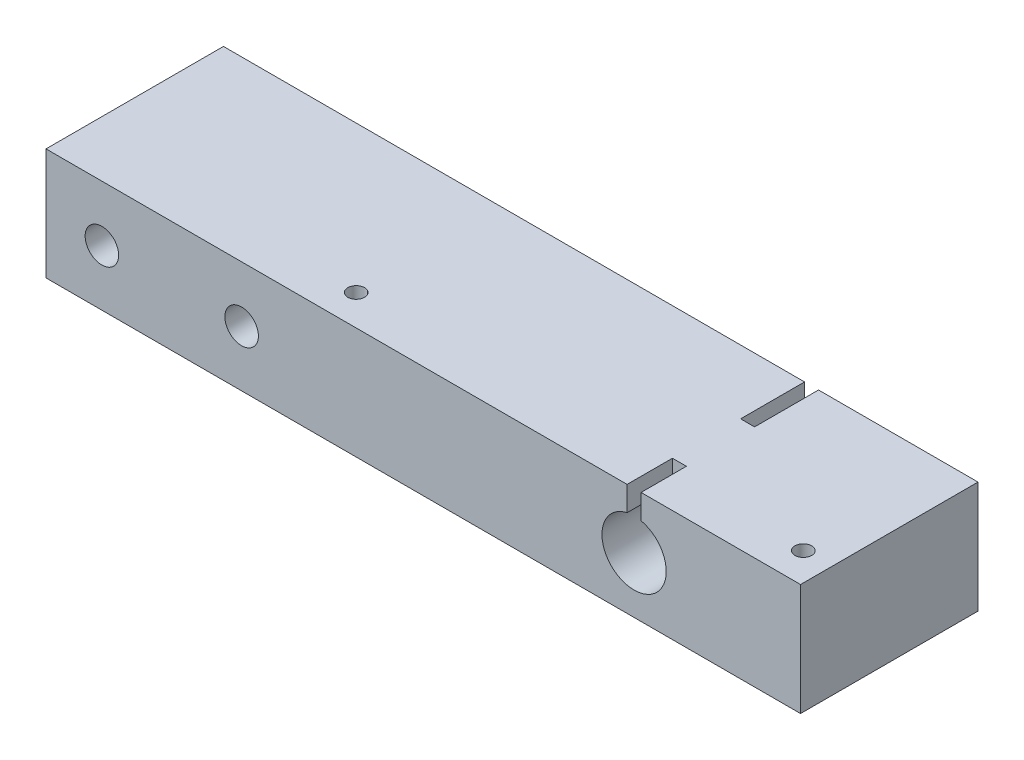
SolidWorks part; units mm, degrees
ref_plane "Front Plane" through (0, 0, 0) normal (0, 0, 1) x (1, 0, 0)
ref_plane "Top Plane" through (0, 0, 0) normal (0, 1, 0) x (1, 0, 0)
ref_plane "Right Plane" through (0, 0, 0) normal (1, 0, 0) x (0, 0, -1)
sketch "Sketch1" plane through (0, 0, 0) normal (0, 0, 1) x (1, 0, 0)
  line L1 (0, 0) -> (54, 0)
  line L2 (0, 0) -> (0, 8)
  line L3 (0, 8) -> (54, 8)
  line L4 (54, 0) -> (54, 8)
extrude "Boss-Extrude1" add sketch "Sketch1" along normal blind 12.7
sketch "Sketch3" plane through (0, 8, 0) normal (0, 1, 0) x (1, 0, 0)
  line L0 (42, -17.996) -> (42, 5.2833) construction
  line L2 (54, -6.35) -> (-1.1589, -6.35) construction
  line L3 (54, -12.7) -> (54, 0) construction
  line L4 (54, -12.7) -> (0, -12.7) construction
  line L5 (42.5877, -12.7) -> (41.5877, -12.7)
  line L6 (42.5877, -12.7) -> (42.5877, -9.4569)
  line L7 (42.5877, -9.4569) -> (41.5877, -9.4569)
  line L8 (41.5877, -12.7) -> (41.5877, -9.4569)
  line L10 (42.5877, 0) -> (41.5877, 0)
  line L11 (42.5877, 0) -> (42.5877, -4.5774)
  line L12 (42.5877, -4.5774) -> (41.5877, -4.5774)
  line L13 (41.5877, 0) -> (41.5877, -4.5774)
extrude "Cut-Extrude1" cut sketch "Sketch3" against normal blind 2
sketch "Sketch4" plane through (0, 0, 12.7) normal (0, 0, 1) x (1, 0, 0)
  line L0 (54, 4) -> (0, 4) construction
  line L1 (54, 0) -> (54, 8) construction
  line L2 (0, 8) -> (0, 0) construction
  line L3 (42.0877, 0) -> (42.0877, 8) construction
  line L4 (42.5877, 0) -> (41.5877, 0) construction
  line L5 (42.5877, 8) -> (41.5877, 8) construction
  circle A0 centre (42.0877, 4) radius 2.3
extrude "Cut-Extrude2" cut sketch "Sketch4" against normal through all
sketch "Sketch5" plane through (0, 8, 0) normal (0, 1, 0) x (1, 0, 0)
  line L0 (54, -10.5) -> (-2.4296, -10.5) construction
  line L1 (54, -12.7) -> (54, 0) construction
  line L2 (52, -19.5209) -> (52, 7.0115) construction
  circle A0 centre (52, -10.5) radius 0.6
  circle A1 centre (20, -10.5) radius 0.6
  dimension "D1" = 32
extrude "Cut-Extrude3" cut sketch "Sketch5" against normal through all
sketch "Sketch6" plane through (0, 0, 12.7) normal (0, 0, 1) x (1, 0, 0)
  line L0 (54, 4) -> (0, 4) construction
  line L1 (54, 0) -> (54, 8) construction
  line L2 (0, 8) -> (0, 0) construction
  line L3 (4, 0) -> (4, 8) construction
  line L4 (0, 0) -> (54, 0) construction
  line L5 (41.5877, 8) -> (0, 8) construction
  circle A0 centre (4, 4) radius 1.2
  circle A1 centre (14, 4) radius 1.2
  dimension "D1" = 10
extrude "Cut-Extrude4" cut sketch "Sketch6" against normal through all
sketch "Sketch10" plane through (0, 8, 0) normal (0, 1, 0) x (1, 0, 0)
  line L0 (54, -6.35) -> (0, -6.35) construction
  line L1 (54, -12.7) -> (54, 0) construction
  line L2 (0, -12.7) -> (0, 0) construction
  line L3 (42.0877, 0) -> (42.0877, -12.7) construction
  line L4 (44.3877, 0) -> (39.7877, 0) construction
  line L5 (39.7877, -12.7) -> (44.3877, -12.7) construction
  line L6 (42.0877, -6.35) -> (36.2418, -12.7) construction
  line L7 (41.5877, -12.7) -> (0, -12.7) construction
  line L8 (42.0877, -6.35) -> (50.7905, -12.7) construction
  line L9 (54, -12.7) -> (42.5877, -12.7) construction
ref_plane "Plane6" through (25.9446, 0, 23.8851) normal (-0.7357, 0, -0.6773) x (-0.6773, 0, 0.7357)
sketch "Sketch12" plane through (25.9446, 0, 23.8851) normal (-0.7357, 0, -0.6773) x (-0.6773, 0, 0.7357)
  line L0 (-23.8344, 8) -> (-19.116, -3.1115) construction
  circle A0 centre (-22.1359, 4) radius 0.6
extrude "Cut-Extrude6" cut sketch "Sketch12" along normal blind 15
sketch "Sketch14" plane through (0, 0, 0) normal (0, 0, -1) x (-1, 0, 0)
  line L0 (-39.7877, 4) -> (-54, 4) construction
  line L1 (-54, 0) -> (-54, 8) construction
  circle A0 centre (-42.0877, 4) radius 2.3 construction
  circle A1 centre (-44.3877, 4) radius 0.6
extrude "Cut-Extrude7" cut sketch "Sketch14" against normal blind 6
